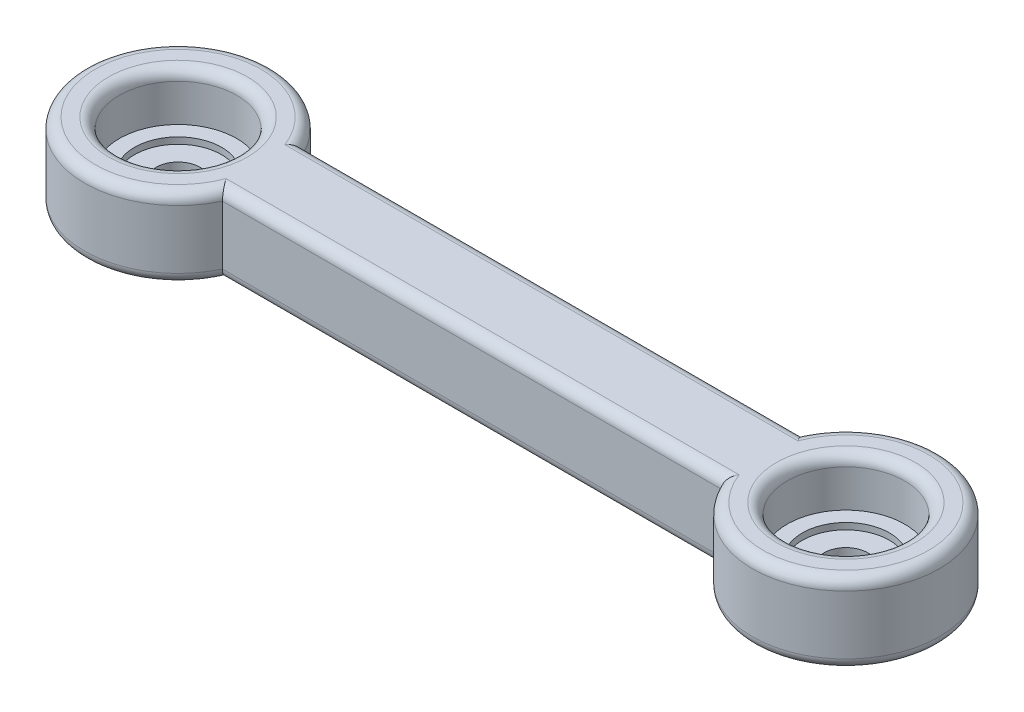
SolidWorks part; units mm, degrees
material "ABS"
ref_plane "Front Plane" through (0, 0, 0) normal (0, 0, 1) x (1, 0, 0)
ref_plane "Top Plane" through (0, 0, 0) normal (0, 1, 0) x (1, 0, 0)
ref_plane "Right Plane" through (0, 0, 0) normal (1, 0, 0) x (0, 0, -1)
sketch "Sketch1" plane through (0, 0, 0) normal (0, 1, 0) x (1, 0, 0)
  line L0 (-46.6886, 7.5) -> (46.6886, 7.5)
  line L1 (-62.5, -7.5) -> (62.5, -7.5) construction
  line L2 (-62.5, -7.5) -> (-62.5, 7.5) construction
  line L3 (-62.5, 7.5) -> (62.5, 7.5) construction
  line L4 (62.5, -7.5) -> (62.5, 7.5) construction
  line L5 (-62.5, -7.5) -> (62.5, 7.5) construction
  line L6 (-62.5, 7.5) -> (62.5, -7.5) construction
  line L7 (-46.6886, -7.5) -> (46.6886, -7.5)
  arc A0 (-46.6886, 7.5) -> (-46.6886, -7.5) centre (-62.5, 0) ccw
  arc A1 (46.6886, -7.5) -> (46.6886, 7.5) centre (62.5, 0) ccw
  circle A2 centre (-62.5, 0) radius 11
  circle A3 centre (62.5, 0) radius 11
  point P0 (0, 0)
  dimension "D1" = 125
  dimension "D2" = 35
  dimension "D4" = 22
  dimension "D3" = 15
extrude "Boss-Extrude1" add sketch "Sketch1" along normal blind 15
sketch "Sketch2" plane through (0, 0, 0) normal (0, 1, 0) x (1, 0, 0)
  circle A0 centre (62.5, 0) radius 11 construction
  circle A1 centre (-62.5, 0) radius 11 construction
  circle A2 centre (62.5, 0) radius 11
  circle A3 centre (-62.5, 0) radius 11
extrude "Boss-Extrude2" add sketch "Sketch2" along normal blind 6
sketch "Sketch3" plane through (0, 6, 0) normal (0, 1, 0) x (1, 0, 0)
  circle A0 centre (-62.5, 0) radius 8.16
  circle A1 centre (62.5, 0) radius 8.16
  dimension "D1" = 16.32
extrude "Cut-Extrude1" cut sketch "Sketch3" against normal blind 1.2
sketch "Sketch4" [suppressed] plane through (0, 0, 0) normal (0, 1, 0) x (1, 0, 0)
  circle A0 centre (-45, 0) radius 11 construction
  circle A1 centre (-45, 0) radius 11
extrude "Boss-Extrude3" [suppressed] add sketch "Sketch4" along normal blind 3
sketch "Sketch5" [suppressed] plane through (0, 6, 0) normal (0, 1, 0) x (1, 0, 0)
  circle A0 centre (-62.5, 0) radius 8.16
  dimension "D1" = 16.32
extrude "Cut-Extrude2" [suppressed] cut sketch "Sketch5" against normal blind 1
sketch "Sketch6" [suppressed] plane through (0, 15, 0) normal (0, 1, 0) x (1, 0, 0)
  circle A0 centre (62.5, 0) radius 11 construction
  circle A1 centre (62.5, 0) radius 11
extrude "Boss-Extrude4" [suppressed] add sketch "Sketch6" against normal blind 3
sketch "Sketch7" [suppressed] plane through (0, 9, 0) normal (0, -1, 0) x (1, 0, 0)
  circle A0 centre (62.5, 0) radius 8.16
  dimension "D1" = 16.32
extrude "Cut-Extrude3" [suppressed] cut sketch "Sketch7" against normal blind 1
sketch "Sketch8" [suppressed] plane through (0, 0, 0) normal (0, 1, 0) x (1, 0, 0)
  circle A0 centre (-50, 0) radius 11 construction
  circle A1 centre (-50, 0) radius 11
  circle A2 centre (50, 0) radius 11 construction
  circle A3 centre (50, 0) radius 11
  circle A4 centre (-50, 0) radius 2.1
  circle A5 centre (50, 0) radius 2.1
  dimension "D1" = 4.2
extrude "Boss-Extrude5" [suppressed] add sketch "Sketch8" along normal up to surface (15 mm away)
fillet "Fillet1" [suppressed] radius 2
fillet "Fillet2" radius 2 10 edges at (0, 0, -7.5) (-80, 0, 0) (0, 0, 7.5) (80, 0, 0) (62.5, 15, 11) (0, 15, 7.5) (-80, 15, 0) (0, 15, -7.5) (80, 15, 0) (-62.5, 15, 11)
fillet "Fillet3" [suppressed] radius 2
sketch "Sketch9" plane through (0, 4.8, 0) normal (0, 1, 0) x (1, 0, 0)
  circle A0 centre (-62.5, 0) radius 4.1
  circle A1 centre (62.5, 0) radius 4.1
  dimension "D1" = 8.2
extrude "Cut-Extrude4" cut sketch "Sketch9" against normal up to surface (4.8 mm away) up to face at (0, 0, 0)
sketch "Sketch10" [suppressed] plane through (0, 5, 0) normal (0, 1, 0) x (1, 0, 0)
  circle A0 centre (-62.5, 0) radius 4.1
  circle A1 centre (62.5, 0) radius 4.1
  dimension "D1" = 8.2
extrude "Cut-Extrude5" [suppressed] cut sketch "Sketch10" against normal through all both and the other way through all
sketch "Sketch11" [suppressed] plane through (0, 0, 0) normal (0, -1, 0) x (1, 0, 0)
  line L1 (-67.2577, -11.6922) -> (67.2577, -11.6922)
  line L2 (-67.2577, -11.6922) -> (-67.2577, 11.6922)
  line L3 (-67.2577, 11.6922) -> (67.2577, 11.6922)
  line L4 (67.2577, -11.6922) -> (67.2577, 11.6922)
  line L5 (-67.2577, -11.6922) -> (67.2577, 11.6922) construction
  line L6 (-67.2577, 11.6922) -> (67.2577, -11.6922) construction
  point P0 (0, 0)
